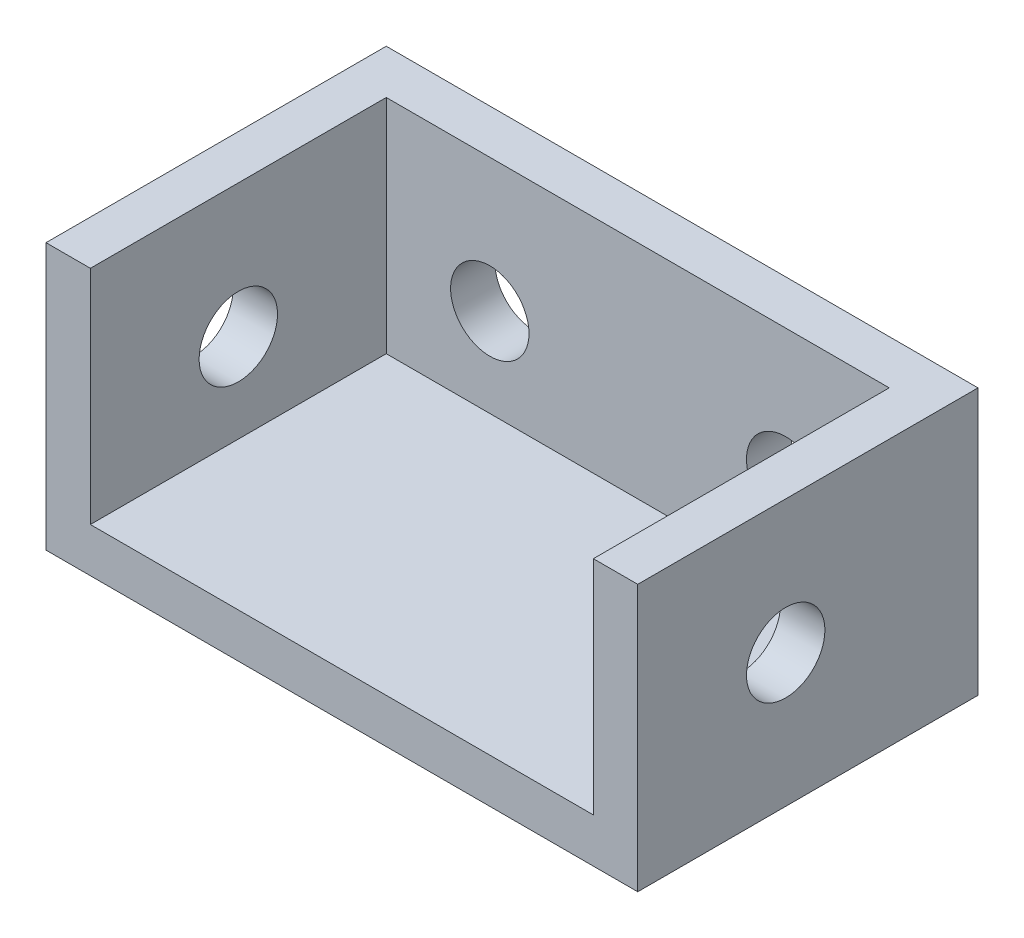
SolidWorks part; units mm, degrees
ref_plane "前视基准面" through (0, 0, 0) normal (0, 0, 1) x (1, 0, 0)
ref_plane "上视基准面" through (0, 0, 0) normal (0, 1, 0) x (1, 0, 0)
ref_plane "右视基准面" through (0, 0, 0) normal (1, 0, 0) x (0, 0, -1)
other "Configuration Table"
sketch "草图1" plane through (0, 0, 0) normal (0, 0, 1) x (1, 0, 0)
  line L0 (-10, 7.3888) -> (-10, -49992.6112) construction
  line L1 (-20, 9) -> (20, 9)
  line L2 (-20, 9) -> (-20, -9)
  line L3 (-20, -9) -> (20, -9)
  line L4 (20, 9) -> (20, -9)
  line L5 (-20, 9) -> (20, -9) construction
  line L6 (-20, -9) -> (20, 9) construction
  line L7 (10, 0.6214) -> (10, -49999.3786) construction
  line L8 (0, 0) -> (50000, 0) construction
  circle A0 centre (-10, 0) radius 2.65
  circle A1 centre (10, 0) radius 2.65
  point P0 (0, 0)
  dimension "D5" = 5.3
  dimension "D6" = 5.3
  dimension "D1" = 18
  dimension "D2" = 40
  dimension "D3" = 10
  dimension "D4" = 10
extrude "凸台-拉伸1" add sketch "草图1" along normal blind 3
sketch "草图3" plane through (-20, 0, 0) normal (-1, 0, 0) x (0, 0, 1)
  line L0 (3, -9) -> (0, -9) construction
  line L1 (3, 9) -> (23, 9)
  line L2 (3, 9) -> (3, -9)
  line L3 (3, -9) -> (23, -9)
  line L4 (23, 9) -> (23, -9)
  line L5 (13, -10) -> (13, 49990) construction
  line L6 (0, 0) -> (50000, 0) construction
  line L9 (3, 9) -> (3, -9) construction
  line L10 (3, 9) -> (0, 9) construction
  circle A0 centre (13, 0) radius 2.65
  point P9 (13, -9)
  point P15 (0, -10)
  dimension "D2" = 5.3
  dimension "D1" = 20
extrude "凸台-拉伸2" add sketch "草图3" against normal blind 40
sketch "草图5" plane through (0, 9, 0) normal (0, 1, 0) x (1, 0, 0)
  line L0 (20, -23) -> (-20, -23) construction
  line L1 (-17, -23) -> (17, -23)
  line L2 (-17, -23) -> (-17, -3)
  line L3 (-17, -3) -> (17, -3)
  line L4 (17, -23) -> (17, -3)
  line L5 (-20, -23) -> (-20, 0) construction
  line L6 (20, 0) -> (-20, 0) construction
  line L7 (20, -23) -> (20, 0) construction
  dimension "D1" = 3
  dimension "D2" = 3
  dimension "D3" = 3
extrude "切除-拉伸2" cut sketch "草图5" against normal blind 15
